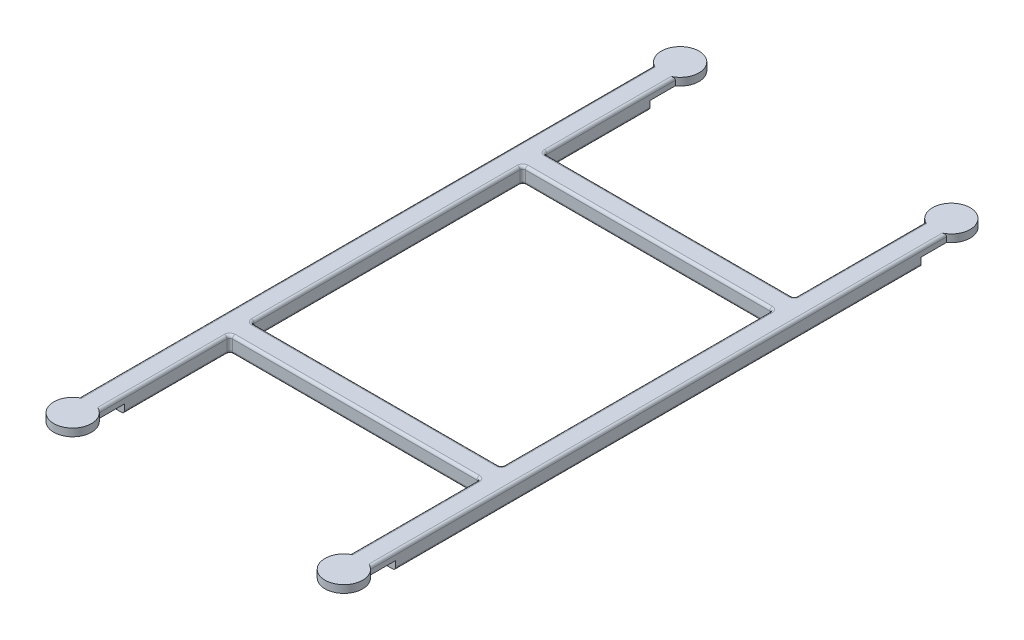
SolidWorks part; units mm, degrees
ref_plane "Front Plane" through (0, 0, 0) normal (0, 0, 1) x (1, 0, 0)
ref_plane "Top Plane" through (0, 0, 0) normal (0, 1, 0) x (1, 0, 0)
ref_plane "Right Plane" through (0, 0, 0) normal (1, 0, 0) x (0, 0, -1)
sketch "Sketch1" plane through (0, 0, 0) normal (0, 1, 0) x (1, 0, 0)
  line L0 (-50, 112) -> (0, 112) construction
  line L1 (-53.95, 0) -> (-53.95, 106.2816)
  line L2 (-53.95, 53.1408) -> (-46.05, 53.1408) construction
  line L3 (-46.05, 0) -> (-46.05, 106.2816)
  line L4 (-50, 105) -> (-50, 53.1408) construction
  line L5 (0, 112) -> (0, 0) construction
  line L7 (-53.95, 0) -> (0, 0) construction
  line L12 (-53.95, 0) -> (-46.05, 0)
  arc A0 (-46.05, 106.2816) -> (-53.95, 106.2816) centre (-50, 112) ccw
  point P12 (-50, 53.1408)
  dimension "D1" = 7.9
  dimension "D2" = 13.9
  dimension "D3" = 50
  dimension "D4" = 112
extrude "Boss-Extrude1" add sketch "Sketch1" along normal blind 6
sketch "Sketch3" plane through (0, 0, 0) normal (0, -1, 0) x (1, 0, 0)
  line L0 (-53.95, -106.2816) -> (-53.95, -96.9)
  line L1 (-53.95, -106.2816) -> (-53.95, 0) construction
  line L2 (-53.95, -96.9) -> (-46.05, -96.9)
  line L3 (-46.05, 0) -> (-46.05, -106.2816) construction
  line L4 (-46.05, -96.9) -> (-46.05, -106.2816)
  arc A0 (-53.95, -106.2816) -> (-46.05, -106.2816) centre (-50, -112) ccw
  arc A1 (-53.95, -106.2816) -> (-46.05, -106.2816) centre (-50, -112) ccw construction
  dimension "D1" = 15.1
extrude "Cut-Extrude1" cut sketch "Sketch3" against normal blind 3.2
sketch "Sketch4" plane through (0, 3.2, 0) normal (0, -1, 0) x (1, 0, 0)
  line L0 (-50, -112) -> (-50, -102) construction
  circle A0 centre (-50, -112) radius 3
  circle A1 centre (-50, -102) radius 2
  dimension "D1" = 10
  dimension "D2" = 6
  dimension "D3" = 4
extrude "Cut-Extrude2" cut sketch "Sketch4" against normal blind 2
mirror "Mirror3" about plane through (0, 0, 0) normal (1, 0, 0) of bodies 128
mirror "Mirror4" about plane through (0, 0, 0) normal (0, 0, 1) of bodies 128 129
sketch "Sketch2" plane through (0, 6, 0) normal (0, 1, 0) x (1, 0, 0)
  line L0 (-53.95, 0) -> (53.95, 0) construction
  line L3 (-46.05, 58) -> (46.05, 58)
  line L6 (46.05, 58) -> (46.05, 50)
  line L7 (46.05, 50) -> (-46.05, 50)
  line L8 (-46.05, 50) -> (-46.05, 58)
  line L9 (46.05, -50) -> (-46.05, -50)
  line L10 (46.05, -58) -> (46.05, -50)
  line L11 (-46.05, -58) -> (46.05, -58)
  line L12 (-46.05, -50) -> (-46.05, -58)
  line L13 (-46.05, -106.2816) -> (-46.05, 106.2816) construction
  line L14 (46.05, -106.2816) -> (46.05, 106.2816) construction
  line L15 (-53.95, 106.2816) -> (-53.95, -106.2816) construction
  line L16 (53.95, 106.2816) -> (53.95, -106.2816) construction
  dimension "D1" = 8
  dimension "D2" = 100
extrude "Boss-Extrude2" add sketch "Sketch2" against normal up to surface (6 mm away) up to face at (-50, 0, 0)
fillet "Fillet1" radius 1 32 edges at (-46.05, 0, 0) (-46.05, 6, 0) (46.05, 3, 50) (46.05, 3, 58) (-46.05, 3, 58) (-46.05, 3, 50) (0, 6, 50) (0, 6, 58) (0, 0, 58) (0, 0, 50) (-53.95, 0, 0) (-53.95, 6, 0) (-46.05, 0, 77.45) (-46.05, 0, -77.45) (-46.05, 6, -82.1408) (-46.05, 3, -50) (-46.05, 3, -58) (46.05, 3, -58) (46.05, 3, -50) (0, 6, -50) (0, 6, -58) (0, 0, -58) (0, 0, -50) (46.05, 6, -82.1408) (46.05, 6, 82.1408) (53.95, 6, 0) (53.95, 0, 0) (46.05, 0, 77.45) (46.05, 0, -77.45) (-46.05, 6, 82.1408) (46.05, 0, 0) (46.05, 6, 0)
